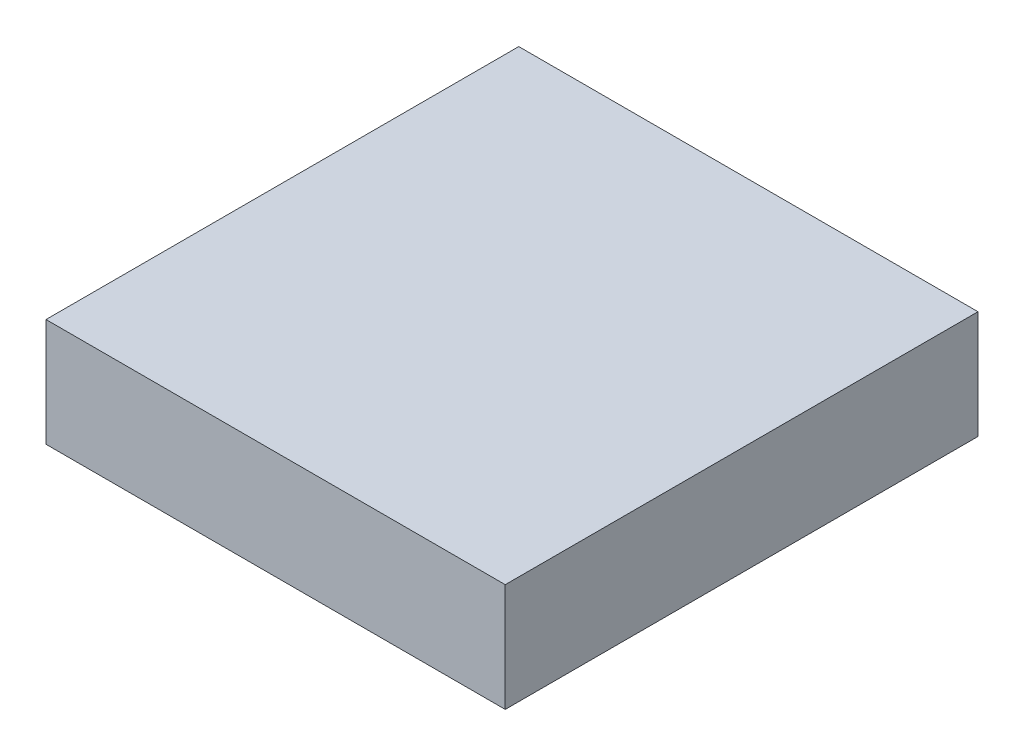
SolidWorks part; units mm, degrees
ref_plane "Front Plane" through (0, 0, 0) normal (0, 0, 1) x (1, 0, 0)
ref_plane "Top Plane" through (0, 0, 0) normal (0, 1, 0) x (1, 0, 0)
ref_plane "Right Plane" through (0, 0, 0) normal (1, 0, 0) x (0, 0, -1)
sketch "Sketch2" plane through (0, 0, 0) normal (0, 1, 0) x (1, 0, 0)
  line L1 (-43.18, 44.45) -> (43.18, 44.45)
  line L2 (-43.18, 44.45) -> (-43.18, -44.45)
  line L3 (-43.18, -44.45) -> (43.18, -44.45)
  line L4 (43.18, 44.45) -> (43.18, -44.45)
  line L5 (-43.18, 44.45) -> (43.18, -44.45) construction
  line L6 (-43.18, -44.45) -> (43.18, 44.45) construction
  point P0 (0, 0)
  dimension "D1" = 88.9
  dimension "D2" = 86.36
extrude "Boss-Extrude1" add sketch "Sketch2" along normal blind 20.32
